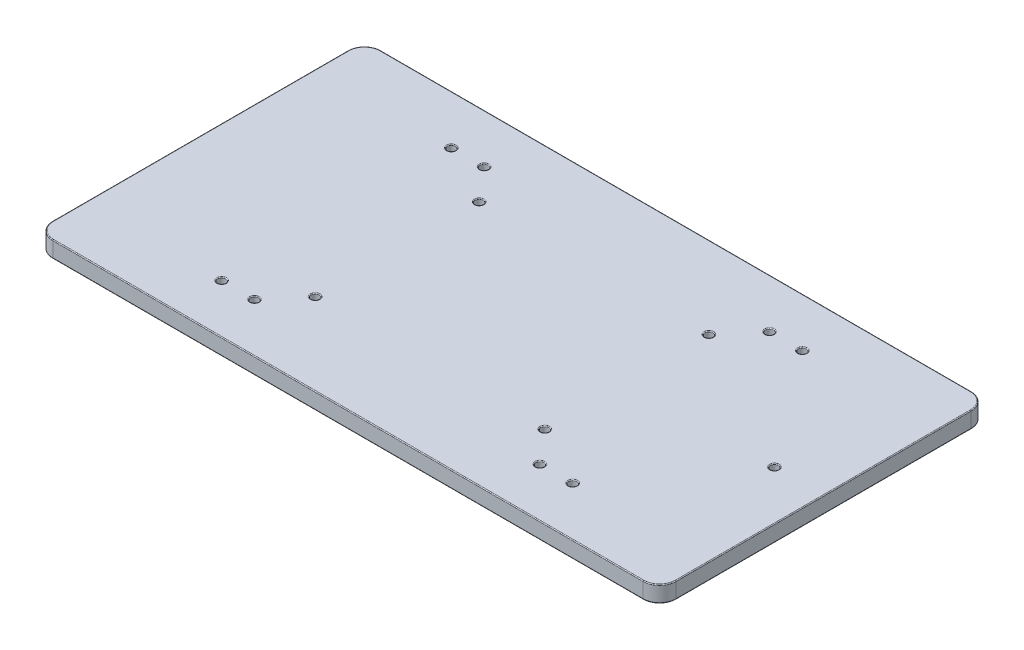
SolidWorks part; units mm, degrees
ref_plane "Front Plane" through (0, 0, 0) normal (0, 0, 1) x (1, 0, 0)
ref_plane "Top Plane" through (0, 0, 0) normal (0, 1, 0) x (1, 0, 0)
ref_plane "Right Plane" through (0, 0, 0) normal (1, 0, 0) x (0, 0, -1)
sketch "Sketch1" plane through (0, 0, 0) normal (0, 1, 0) x (1, 0, 0)
  line L0 (80, 50) -> (80, -50) construction
  line L1 (-95, 50) -> (95, 50)
  line L2 (-95, 50) -> (-95, -50)
  line L3 (-95, -50) -> (95, -50)
  line L4 (95, 50) -> (95, -50)
  line L5 (-95, 50) -> (95, -50) construction
  line L6 (-95, -50) -> (95, 50) construction
  line L7 (-35, 25) -> (35, 25)
  line L8 (-35, 25) -> (-35, -25)
  line L9 (-35, -25) -> (35, -25)
  line L10 (35, 25) -> (35, -25)
  line L11 (-35, 25) -> (35, -25) construction
  line L12 (-35, -25) -> (35, 25) construction
  line L13 (0, 0) -> (45.2733, 0) construction
  line L14 (0, 0) -> (0, 31.0742) construction
  circle A0 centre (-35, 25) radius 1.25
  circle A1 centre (35, 25) radius 1.25
  circle A2 centre (35, -25) radius 1.25
  circle A3 centre (-35, -25) radius 1.25
  circle A4 centre (80, 0) radius 1.25
  circle A5 centre (-53.5, -35) radius 1.25
  circle A6 centre (-43.5, -35) radius 1.25
  circle A7 centre (43.5, -35) radius 1.25
  circle A8 centre (53.5, -35) radius 1.25
  circle A9 centre (53.5, 35) radius 1.25
  circle A10 centre (43.5, 35) radius 1.25
  circle A11 centre (-43.5, 35) radius 1.25
  circle A12 centre (-53.5, 35) radius 1.25
  point P0 (0, 0)
  point P6 (0, 0)
  point P34 (-53.5, 35)
  dimension "D5" = 2.5
  dimension "D7" = 2.5
  dimension "D8" = 2.5
  dimension "D1" = 190
  dimension "D2" = 100
  dimension "D3" = 70
  dimension "D4" = 50
  dimension "D6" = 15
  dimension "D9" = 10
  dimension "D10" = 43.5
  dimension "D11" = 15
extrude "Boss-Extrude1" add sketch "Sketch1" along normal blind 5 contours L4 L1 L2 L3 A11 A10 A9 A7 A6 A5 A4 A3 L8 A0 L7 A1 L10 A2 L9 A8 A12 | A3 L9 A2 L10 A1 L7 A0 L8
fillet "Fillet1" radius 5 4 edges at (-95, 2.5, 50) (95, 2.5, 50) (95, 2.5, -50) (-95, 2.5, -50)
fillet "Fillet2" radius 0.25 42 edges at (-35, 0, 26.25) (35, 0, -23.75) (35, 0, 26.25) (-43.5, 0, -33.75) (43.5, 0, -33.75) (53.5, 0, -33.75) (43.5, 0, 36.25) (-43.5, 0, 36.25) (-53.5, 0, 36.25) (80, 0, 1.25) (-35, 0, -23.75) (95, 0, 0) (0, 0, -50) (-95, 0, 0) (0, 0, 50) (53.5, 0, 36.25) (-53.5, 0, -33.75) (-35, 5, 26.25) (35, 5, -23.75) (35, 5, 26.25) (-43.5, 5, -33.75) (43.5, 5, -33.75) (53.5, 5, -33.75) (43.5, 5, 36.25) (-43.5, 5, 36.25) (-53.5, 5, 36.25) (80, 5, 1.25) (-35, 5, -23.75) (95, 5, 0) (0, 5, -50) (-95, 5, 0) (53.5, 5, 36.25) (-53.5, 5, -33.75) (-93.5355, 0, -48.5355) (93.5355, 0, -48.5355) (93.5355, 0, 48.5355) (-93.5355, 0, 48.5355) (-93.5355, 5, -48.5355) (93.5355, 5, -48.5355) (93.5355, 5, 48.5355) (-93.5355, 5, 48.5355) (0, 5, 50)
